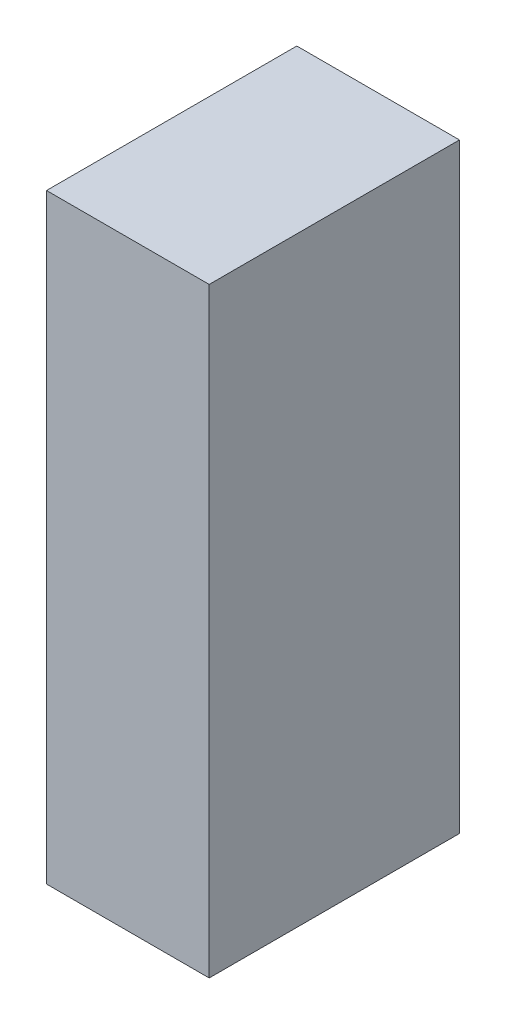
SolidWorks part; units mm, degrees
ref_plane "Plan de face" through (0, 0, 0) normal (0, 0, 1) x (1, 0, 0)
ref_plane "Plan de dessus" through (0, 0, 0) normal (0, 1, 0) x (1, 0, 0)
ref_plane "Plan de droite" through (0, 0, 0) normal (1, 0, 0) x (0, 0, -1)
sketch "Esquisse1" plane through (0, 0, 0) normal (0, 0, 1) x (1, 0, 0)
  line L1 (0, 0) -> (-65, 0)
  line L2 (0, 0) -> (0, 240)
  line L3 (0, 240) -> (-65, 240)
  line L4 (-65, 0) -> (-65, 240)
  dimension "D1" = 240
  dimension "D2" = 65
extrude "Boss.-Extru.1" add sketch "Esquisse1" along normal blind 100
